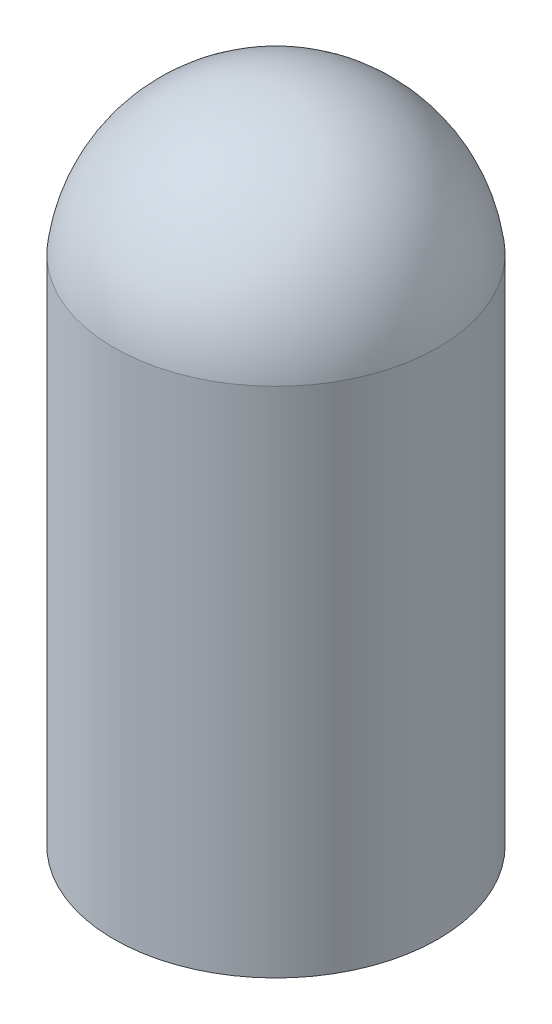
SolidWorks part; units mm, degrees
material "Glass"
ref_plane "Front Plane" through (0, 0, 0) normal (0, 0, 1) x (1, 0, 0)
ref_plane "Top Plane" through (0, 0, 0) normal (0, 1, 0) x (1, 0, 0)
ref_plane "Right Plane" through (0, 0, 0) normal (1, 0, 0) x (0, 0, -1)
sketch "Sketch1" plane through (0, 0, 0) normal (0, 0, 1) x (1, 0, 0)
  line L0 (-39.6875, 0) -> (39.6875, 0) construction
  line L1 (-39.6875, 0) -> (-39.6875, 125.476)
  line L2 (0, 0) -> (0, 165.1) construction
  line L3 (-35.8775, 0) -> (-35.8775, 125.2394)
  line L4 (-39.6875, 0) -> (-35.8775, 0)
  line L5 (0, 160.6298) -> (0, 156.8198)
  arc A0 (-39.6875, 125.476) -> (0, 160.6298) centre (0, 120.65) cw
  arc A1 (-35.8775, 125.2394) -> (0, 156.8198) centre (0, 120.65) cw
  point P4 (0, 0)
  dimension "D1" = 79.375
  dimension "D2" = 165.1
  dimension "D3" = 125.476
  dimension "D4" = 3.81
revolve "Revolve1" add sketch "Sketch1" angle 360 about L2
